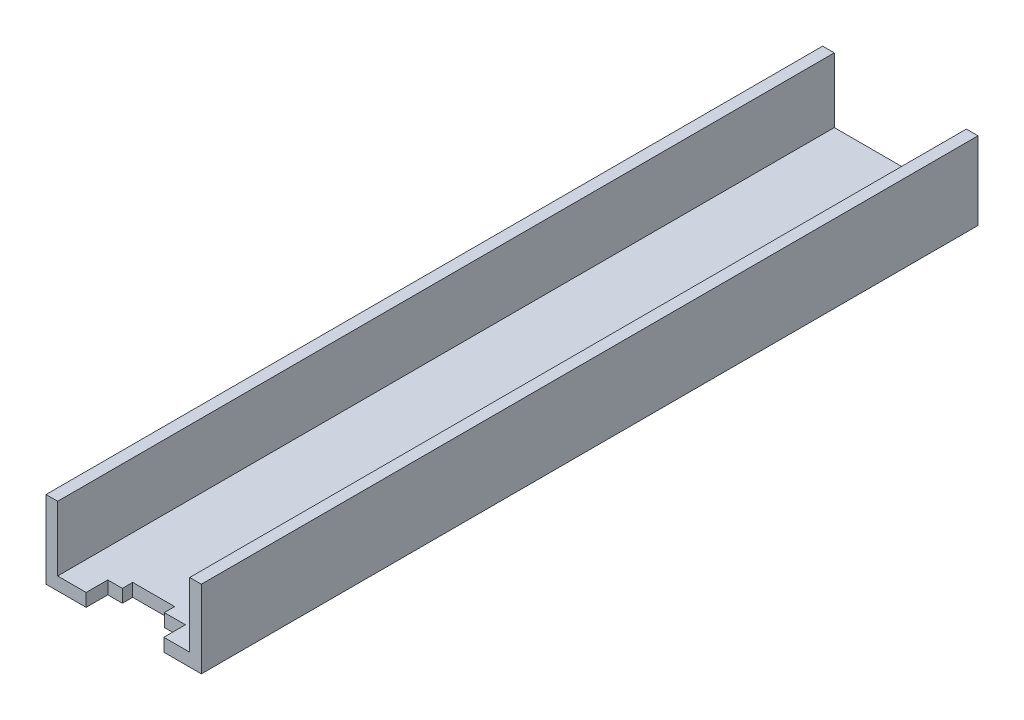
SolidWorks part; units mm, degrees
ref_plane "前基準面" through (0, 0, 0) normal (0, 0, 1) x (1, 0, 0)
ref_plane "上基準面" through (0, 0, 0) normal (0, 1, 0) x (1, 0, 0)
ref_plane "右基準面" through (0, 0, 0) normal (1, 0, 0) x (0, 0, -1)
sketch "草圖1" plane through (0, 0, 0) normal (0, 0, 1) x (1, 0, 0)
  line L1 (-3, 1.5) -> (3, 1.5)
  line L2 (-3, 1.5) -> (-3, -1.5)
  line L3 (-3, -1.5) -> (3, -1.5)
  line L4 (3, 1.5) -> (3, -1.5)
  line L5 (-3, 1.5) -> (3, -1.5) construction
  line L6 (-3, -1.5) -> (3, 1.5) construction
  point P0 (0, 0)
extrude "填料-伸長1" add sketch "草圖1" along normal blind 30 contours L1 L4 L3 L2
sketch "草圖2" plane through (0, 0, 30) normal (0, 0, 1) x (1, 0, 0)
  line L0 (-3, -1.5) -> (3, -1.5) construction
  line L1 (-3, 1.5) -> (-2.55, 1.5)
  line L2 (-3, 1.5) -> (-3, -1.5)
  line L3 (-3, -1.5) -> (-2.55, -1.5)
  line L4 (-2.55, 1.5) -> (-2.55, -1.5)
sketch "草圖3" plane through (0, 0, 30) normal (0, 0, 1) x (1, 0, 0)
  line L1 (3, -1.5) -> (-2.55, -1.5)
  line L2 (3, -1.5) -> (3, -1)
  line L3 (3, -1) -> (-2.55, -1)
  line L4 (-2.55, -1.5) -> (-2.55, -1)
  point P5 (0, 0)
sketch "草圖4" plane through (0, 0, 30) normal (0, 0, 1) x (1, 0, 0)
  line L1 (-2.55, 1.5) -> (2.55, 1.5)
  line L2 (-2.55, 1.5) -> (-2.55, -1)
  line L3 (-2.55, -1) -> (2.55, -1)
  line L4 (2.55, 1.5) -> (2.55, -1)
extrude "除料-伸長1" cut sketch "草圖4" against normal blind 30 contours L4 L3 L2 L1
sketch "草圖5" plane through (0, -1.5, 0) normal (0, -1, 0) x (-1, 0, 0)
  line L1 (3, -30) -> (1.45, -30)
  line L2 (3, -30) -> (3, -28.2454)
  line L3 (3, -28.2454) -> (1.45, -28.2454)
  line L4 (1.45, -30) -> (1.45, -28.2454)
sketch "草圖6" plane through (0, -1.5, 0) normal (0, -1, 0) x (-1, 0, 0)
  line L1 (1.45, -30) -> (-1.55, -30)
  line L2 (1.45, -30) -> (1.45, -29.1636)
  line L3 (1.45, -29.1636) -> (-1.55, -29.1636)
  line L4 (-1.55, -30) -> (-1.55, -29.1636)
extrude "除料-伸長2" cut sketch "草圖6" against normal blind 0.5
sketch "草圖7" plane through (0, -1.5, 0) normal (0, -1, 0) x (-1, 0, 0)
  line L1 (1.45, -29.1636) -> (0.8866, -29.1636)
  line L2 (1.45, -29.1636) -> (1.45, -28.2118)
  line L3 (1.45, -28.2118) -> (0.8866, -28.2118)
  line L4 (0.8866, -29.1636) -> (0.8866, -28.2118)
sketch "草圖8" plane through (0, -1.5, 0) normal (0, -1, 0) x (-1, 0, 0)
  line L1 (0.8866, -29.1636) -> (-0.7334, -29.1636)
  line L2 (0.8866, -29.1636) -> (0.8866, -28.7636)
  line L3 (0.8866, -28.7636) -> (-0.7334, -28.7636)
  line L4 (-0.7334, -29.1636) -> (-0.7334, -28.7636)
extrude "除料-伸長3" cut sketch "草圖8" against normal blind 0.5 contours L3 L4 L1 L2
